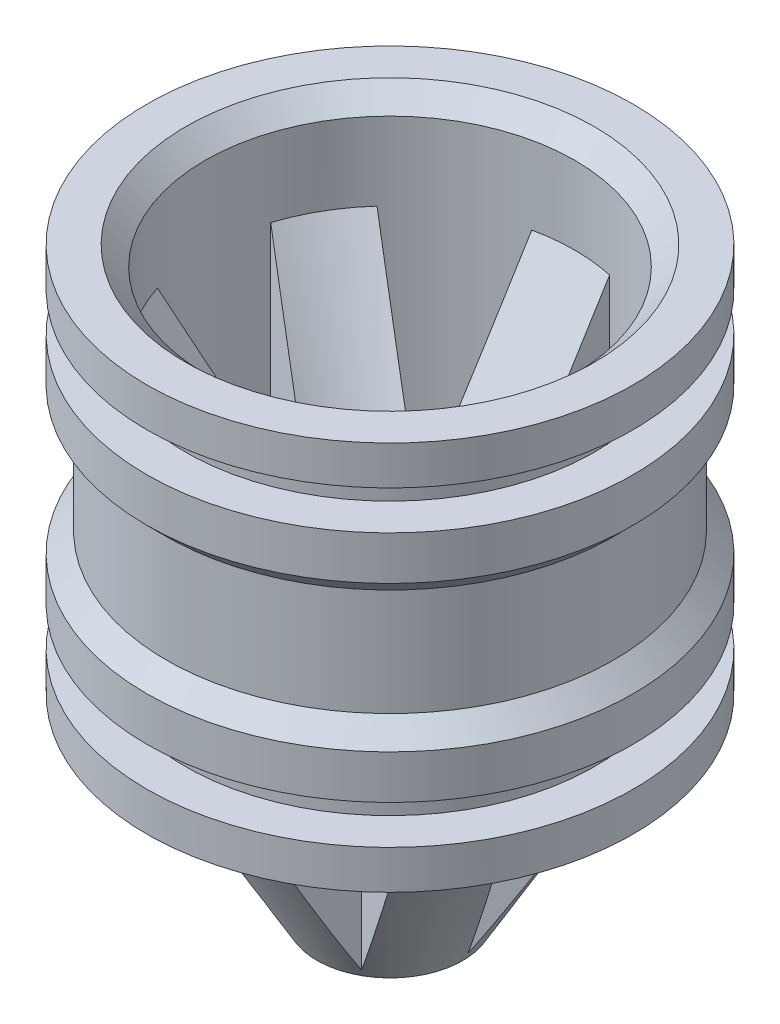
SolidWorks part; units mm, degrees
ref_plane "Front Plane" through (0, 0, 0) normal (0, 0, 1) x (1, 0, 0)
ref_plane "Top Plane" through (0, 0, 0) normal (0, 1, 0) x (1, 0, 0)
ref_plane "Right Plane" through (0, 0, 0) normal (1, 0, 0) x (0, 0, -1)
sketch "Sketch1" plane through (0, 0, 0) normal (0, 1, 0) x (1, 0, 0)
  circle A0 centre (0, 0) radius 15.875
  dimension "D1" = 31.75
extrude "Boss-Extrude1" add sketch "Sketch1" along normal blind 25.4
sketch "Sketch2" plane through (0, 25.4, 0) normal (0, 1, 0) x (1, 0, 0)
  circle A0 centre (0, 0) radius 1.35
  dimension "D1" = 2.7
extrude "Cut-Extrude2" cut sketch "Sketch2" against normal up to surface (25.4 mm away) up to face at (0, 0, 15.875)
ref_plane "Plane1" through (0, 0, 0) normal (0, 0, 1) x (1, 0, 0)
sketch "Sketch3" plane through (0, 0, 0) normal (0, 0, 1) x (1, 0, 0)
  line L1 (0, 0) -> (0, -12.7)
  line L3 (-15.875, 0) -> (0, 0)
  line L4 (-4.7625, -12.7) -> (0, -12.7)
  line L5 (-15.875, 0) -> (-10.2048, -3.2737)
  line L6 (-10.2048, -3.2737) -> (-4.7625, -12.7)
  point P10 (0, -12.7)
  dimension "D3" = 30
  dimension "D4" = 60
  dimension "D1" = 12.7
  dimension "D2" = 4.7625
revolve "Revolve2" add sketch "Sketch3" angle 360 about L1
sketch "Sketch4" plane through (0, -12.7, 0) normal (0, -1, 0) x (1, 0, 0)
  line L0 (1.4124, -2.6467) -> (2.9876, 0.272)
  arc A1 (1.4124, -2.6467) -> (2.9876, 0.272) centre (0, 0) cw
  circle A4 centre (0, 0) radius 4.7625 construction
  dimension "D1" = 3
  dimension "D2" = 2.5
extrude "Cut-Extrude3" cut sketch "Sketch4" against normal blind 12.7
sketch "Sketch5" plane through (0, 0, 0) normal (0, 0, 1) x (1, 0, 0)
  line L0 (-15.875, 25.4) -> (-15.875, 0) construction
  line L1 (15.875, 25.4) -> (-15.875, 25.4) construction
  line L2 (-12.065, 24.13) -> (-12.065, 19.05)
  line L3 (-12.065, 19.05) -> (-6.35, 9.525)
  line L4 (-3.175, 6.35) -> (0, 6.35)
  line L5 (-3.175, 6.35) -> (-3.175, 9.525)
  line L7 (0, 6.35) -> (0, 25.4)
  line L8 (-15.875, 0) -> (15.875, 0) construction
  line L9 (0, 25.4) -> (-13.335, 25.4)
  line L10 (-3.175, 9.525) -> (-6.35, 9.525)
  line L11 (-12.065, 24.13) -> (-13.335, 25.4)
  dimension "D1" = 3.81
  dimension "D2" = 6.35
  dimension "D3" = 1.27
  dimension "D4" = 3.175
  dimension "D5" = 3.175
  dimension "D6" = 1.27
  dimension "D7" = 6.35
  dimension "D8" = 6.35
revolve "Cut-Revolve1" cut sketch "Sketch5" angle 360 about L7
ref_plane "Plane2" through (0, 19.05, 0) normal (0, 1, 0) x (1, 0, 0)
sketch "Sketch6" plane through (0, 19.05, 0) normal (0, 1, 0) x (1, 0, 0)
  line L8 (-5.08, 0) -> (-11.4844, 3.6976)
  line L9 (-5.08, 0) -> (-11.4844, -3.6976)
  line L10 (-2.54, 4.3994) -> (-2.54, 11.7946)
  line L11 (-2.54, 4.3994) -> (-8.9444, 8.097)
  line L12 (2.54, 4.3994) -> (8.9444, 8.097)
  line L13 (2.54, 4.3994) -> (2.54, 11.7946)
  line L14 (5.08, 0) -> (11.4844, -3.6976)
  line L15 (5.08, 0) -> (11.4844, 3.6976)
  line L16 (2.54, -4.3994) -> (2.54, -11.7946)
  line L17 (2.54, -4.3994) -> (8.9444, -8.097)
  line L21 (-8.9444, -8.097) -> (-2.54, -4.3994)
  line L22 (-2.54, -4.3994) -> (-2.54, -11.7946)
  line L24 (-2.54, -4.3994) -> (2.54, -4.3994)
  line L25 (2.54, -4.3994) -> (5.08, 0)
  line L26 (5.08, 0) -> (2.54, 4.3994)
  line L27 (2.54, 4.3994) -> (-2.54, 4.3994)
  line L28 (-2.54, 4.3994) -> (-5.08, 0)
  line L29 (-5.08, 0) -> (-2.54, -4.3994)
  circle A0 centre (0, 0) radius 4.3994 construction
  circle A1 centre (0, 0) radius 12.065 construction
  circle A2 centre (0, 0) radius 12.065 construction
  arc A3 (-8.9444, -8.097) -> (-2.54, -11.7946) centre (0, 0) ccw
  arc A4 (-11.4844, 3.6976) -> (-11.4844, -3.6976) centre (0, 0) ccw
  arc A5 (-2.54, 11.7946) -> (-8.9444, 8.097) centre (0, 0) ccw
  arc A6 (8.9444, 8.097) -> (2.54, 11.7946) centre (0, 0) ccw
  arc A7 (11.4844, -3.6976) -> (11.4844, 3.6976) centre (0, 0) ccw
  arc A8 (2.54, -11.7946) -> (8.9444, -8.097) centre (0, 0) ccw
  circle A9 centre (0, 0) radius 3.175 construction
  point P33 (0, 0)
  dimension "D2" = 90
  dimension "D1" = 5.08
  dimension "D3" = 90
  dimension "D5" = 6
extrude "Cut-Extrude5" cut sketch "Sketch6" against normal through all contours L8 A4 L9 | L10 A5 L11 | L12 A6 L13 | L14 A7 L15 | L16 A8 L17 | L21 A3 L22
sketch "Sketch7" plane through (0, 0, 0) normal (0, 0, 1) x (1, 0, 0)
  line L0 (-15.875, 25.4) -> (-15.875, 0) construction
  line L1 (-15.875, 22.86) -> (-13.335, 22.86)
  line L2 (-15.875, 22.86) -> (-15.875, 20.32)
  line L3 (-15.875, 20.32) -> (-13.335, 20.32)
  line L4 (-13.335, 22.86) -> (-13.335, 20.32)
  line L5 (0, 0) -> (0, 25.4) construction
  line L6 (-15.875, 2.54) -> (-13.335, 2.54)
  line L7 (-15.875, 2.54) -> (-15.875, 5.08)
  line L8 (-15.875, 5.08) -> (-13.335, 5.08)
  line L9 (-13.335, 2.54) -> (-13.335, 5.08)
  line L11 (-15.875, 17.4625) -> (-15.875, 7.9375)
  line L13 (-14.605, 16.1925) -> (-14.605, 9.2075)
  line L14 (15.875, 25.4) -> (-15.875, 25.4) construction
  line L15 (-15.875, 17.4625) -> (-14.605, 16.1925)
  line L17 (-14.605, 9.2075) -> (-15.875, 7.9375)
  line L19 (-15.875, 0) -> (15.875, 0) construction
  point P11 (-14.605, 7.9375)
  point P13 (-14.605, 17.4625)
  point P22 (0, 12.7)
  point P26 (-14.605, 12.7)
  dimension "D1" = 2.54
  dimension "D2" = 2.54
  dimension "D3" = 2.54
  dimension "D4" = 2.54
  dimension "D5" = 6.985
  dimension "D6" = 9.525
  dimension "D7" = 45
revolve "Cut-Revolve2" cut sketch "Sketch7" angle 360 about L5
